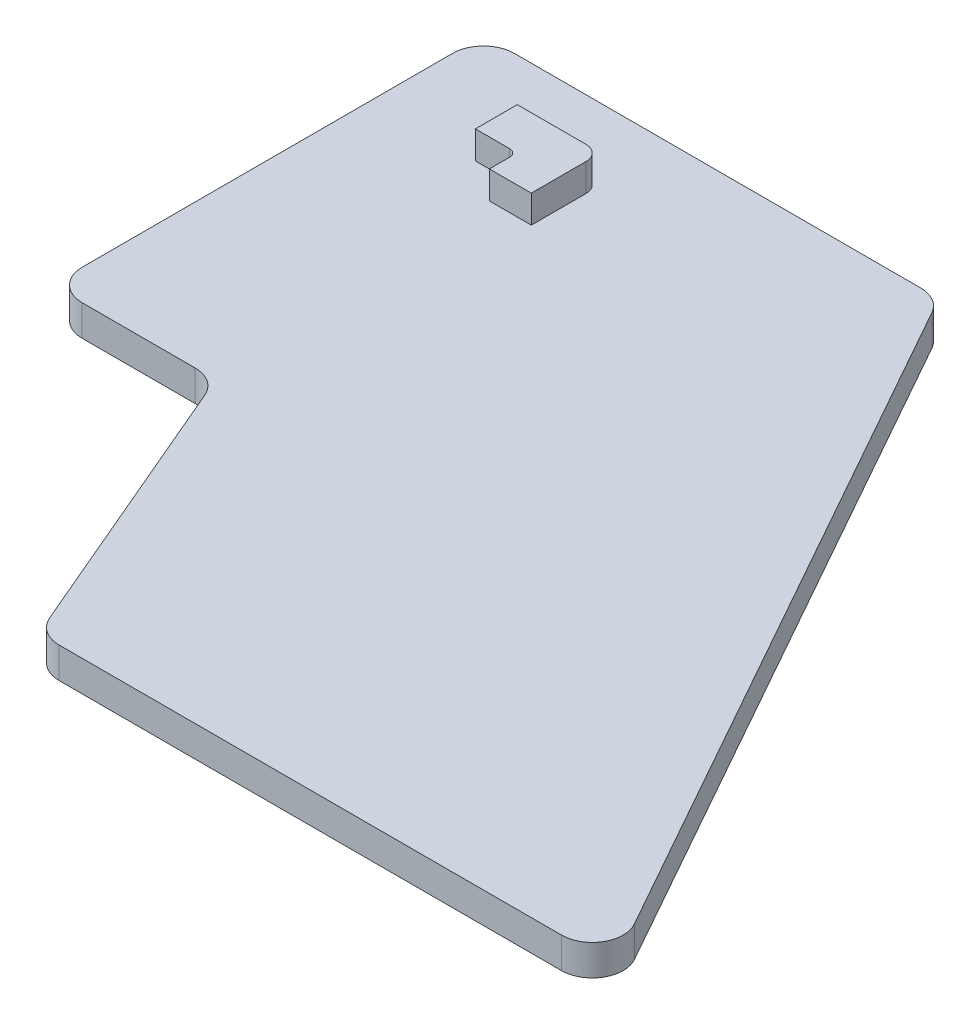
SolidWorks part; units mm, degrees
ref_plane "Front Plane" through (0, 0, 0) normal (0, 0, 1) x (1, 0, 0)
ref_plane "Top Plane" through (0, 0, 0) normal (0, 1, 0) x (1, 0, 0)
ref_plane "Right Plane" through (0, 0, 0) normal (1, 0, 0) x (0, 0, -1)
sketch "Sketch1" plane through (0, 0, 0) normal (0, 1, 0) x (1, 0, 0)
  line L0 (3.175, 44.5079) -> (45.0475, 44.5079)
  line L1 (47.8162, 42.8869) -> (87.0385, -26.992)
  line L2 (84.2699, -31.7211) -> (32.5289, -31.7211)
  line L3 (29.6083, -29.7913) -> (17.7293, -1.9298)
  line L4 (14.8087, 0) -> (3.175, 0)
  line L5 (0, 3.175) -> (0, 41.3329)
  arc A12 (45.0475, 44.5079) -> (47.8162, 42.8869) centre (45.0475, 41.3329) cw
  arc A13 (87.0385, -26.992) -> (84.2699, -31.7211) centre (84.2699, -28.5461) cw
  arc A14 (32.5289, -31.7211) -> (29.6083, -29.7913) centre (32.5289, -28.5461) cw
  arc A15 (17.7293, -1.9298) -> (14.8087, 0) centre (14.8087, -3.175) ccw
  arc A16 (3.175, 0) -> (0, 3.175) centre (3.175, 3.175) cw
  arc A17 (3.175, 44.5079) -> (0, 41.3329) centre (3.175, 41.3329) ccw
  point P54 (0, 0)
  dimension "D2" = 3.175
extrude "Extrude1" add sketch "Sketch1" against normal blind 3.175
sketch "Sketch4" plane through (0, 0, 0) normal (0, 1, 0) x (1, 0, 0)
  line L0 (3.175, 0) -> (14.8087, 0) construction
  line L1 (10.7688, 37.225) -> (17.8545, 37.225)
  line L6 (15.0618, 32.1463) -> (15.0618, 30.0552)
  line L7 (15.0618, 30.0552) -> (19.3785, 30.0552)
  line L8 (19.3785, 35.701) -> (19.3785, 30.0552)
  line L11 (14.2998, 32.9083) -> (10.7688, 32.9083)
  line L12 (10.7688, 37.225) -> (10.7688, 32.9083)
  arc A0 (15.0618, 32.1463) -> (14.2998, 32.9083) centre (14.2998, 32.1463) ccw
  arc A1 (17.8545, 37.225) -> (19.3785, 35.701) centre (17.8545, 35.701) cw
  point P36 (38.5454, 14.2917)
  point P37 (64.2782, -17.0156)
  point P38 (41.581, -9.2207)
  dimension "D1" = 0.762
  dimension "D4" = 1.524
  dimension "D2" = 32.9083
  dimension "D3" = 32.9083
extrude "Extrude2" add sketch "Sketch4" along normal mid plane 5.715
